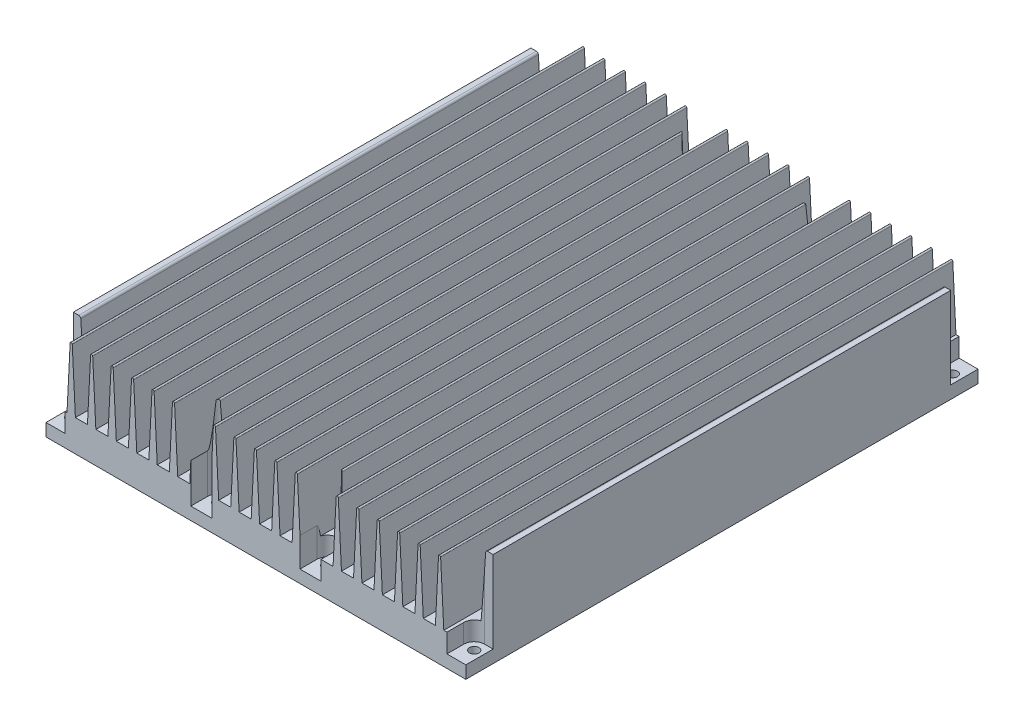
SolidWorks part; units mm, degrees
ref_plane "Спереди" through (0, 0, 0) normal (0, 0, 1) x (1, 0, 0)
ref_plane "Сверху" through (0, 0, 0) normal (0, 1, 0) x (1, 0, 0)
ref_plane "Справа" through (0, 0, 0) normal (1, 0, 0) x (0, 0, -1)
sketch "Эскиз1" plane through (0, 0, 0) normal (0, 0, 1) x (1, 0, 0)
  line L0 (0, 45) -> (2.5644, 45)
  line L1 (0, 0) -> (200, 0)
  line L2 (3.5622, 44.0665) -> (5.5, 15)
  line L3 (0, 45) -> (0, 0)
  line L4 (200, 45) -> (200, 0)
  line L5 (100, 63.7127) -> (100, -22.2582) construction
  line L8 (200, 45) -> (197.4356, 45)
  line L9 (196.4378, 44.0665) -> (194.5, 15)
  line L10 (5.5, 15) -> (194.5, 15)
  arc A0 (2.5644, 45) -> (3.5622, 44.0665) centre (2.5644, 44) cw
  arc A2 (197.4356, 45) -> (196.4378, 44.0665) centre (197.4356, 44) ccw
  point P18 (196.5, 45)
  dimension "D9" = 1
  dimension "D1" = 200
  dimension "D2" = 15
  dimension "D3" = 45
  dimension "D4" = 5.5
  dimension "D7" = 3.5
extrude "Вытянуть1" add sketch "Эскиз1" along normal blind 244
sketch "Эскиз2" plane through (0, 0, 244) normal (0, 0, 1) x (1, 0, 0)
  line L0 (194.5, 15) -> (5.5, 15) construction
  line L1 (11.5, 44.5) -> (10, 15)
  line L2 (12, 44.5) -> (12, 22.5548) construction
  line L3 (12.5, 44.5) -> (14, 15)
  line L4 (10, 15) -> (14, 15)
  line L6 (0, 45) -> (0, 0) construction
  arc A0 (11.5, 44.5) -> (12.5, 44.5) centre (12, 44.5) cw
  dimension "D1" = 30
  dimension "D3" = 0.5
  dimension "D2" = 4
  dimension "D4" = 12
  dimension "D5" = 1
extrude "Вытянуть3" add sketch "Эскиз2" against normal blind 244
pattern_curve "Кривая1" of "Вытянуть3" along edge at (100, 0, 0) parameters "D1"=19, "D3"=9.75, "D2"=1, "D4"=50
sketch "Эскиз3" plane through (0, 0, 0) normal (0, -1, 0) x (1, 0, 0)
  line L0 (11.9208, 236) -> (163.4793, 236) construction
  line L9 (4, 8) -> (74, 8) construction
  line L10 (-13.0453, 122) -> (213.0453, 122) construction
  line L11 (0, 244) -> (200, 244) construction
  line L12 (0, 0) -> (200, 0) construction
  line L13 (100, 122) -> (100, 199.2779) construction
  line L14 (0, 244) -> (0, 0) construction
  line L15 (200, 244) -> (200, 0) construction
  line L16 (4, 8) -> (4, 236) construction
  circle A0 centre (4, 236) radius 2.25
  circle A1 centre (74, 236) radius 2.25
  circle A2 centre (74, 8) radius 2.25
  circle A3 centre (4, 8) radius 2.25
  circle A4 centre (196, 8) radius 2.25
  circle A5 centre (126, 8) radius 2.25
  circle A6 centre (126, 236) radius 2.25
  circle A7 centre (196, 236) radius 2.25
  dimension "D2" = 70
  dimension "D4" = 4.5
  dimension "D1" = 228
  dimension "D3" = 70
  dimension "D5" = 4
extrude "Вырез-Вытянуть1" cut sketch "Эскиз3" against normal blind 50
ref_plane "Плоскость1" through (0, 6, 0) normal (0, -1, 0) x (1, 0, 0)
sketch "Эскиз6" plane through (0, 6, 0) normal (0, -1, 0) x (1, 0, 0)
  line L0 (-60.3162, 122) -> (260.3162, 122) construction
  line L1 (0, 244) -> (200, 244) construction
  line L2 (0, 0) -> (200, 0) construction
  line L3 (100, 122) -> (100, 228.6897) construction
  line L4 (0, 244) -> (0, 0) construction
  line L5 (200, 244) -> (200, 0) construction
  line L6 (9, 236) -> (9, 247.6253)
  line L7 (4, 231) -> (-6.1278, 231)
  line L8 (-6.1278, 231) -> (-6.1278, 247.6253)
  line L9 (-6.1278, 247.6253) -> (9, 247.6253)
  line L10 (69, 236) -> (69, 248.9831)
  line L11 (69, 248.9831) -> (79, 248.9831)
  line L12 (79, 248.9831) -> (79, 236)
  line L13 (121, 248.9831) -> (121, 236)
  line L14 (131, 248.9831) -> (121, 248.9831)
  line L15 (131, 236) -> (131, 248.9831)
  line L16 (206.1278, 247.6253) -> (191, 247.6253)
  line L17 (206.1278, 231) -> (206.1278, 247.6253)
  line L18 (196, 231) -> (206.1278, 231)
  line L19 (191, 236) -> (191, 247.6253)
  line L20 (191, 8) -> (191, -3.6253)
  line L21 (196, 13) -> (206.1278, 13)
  line L22 (206.1278, 13) -> (206.1278, -3.6253)
  line L23 (206.1278, -3.6253) -> (191, -3.6253)
  line L24 (131, 8) -> (131, -4.9831)
  line L25 (131, -4.9831) -> (121, -4.9831)
  line L26 (121, -4.9831) -> (121, 8)
  line L27 (79, -4.9831) -> (79, 8)
  line L28 (69, -4.9831) -> (79, -4.9831)
  line L29 (69, 8) -> (69, -4.9831)
  line L30 (-6.1278, -3.6253) -> (9, -3.6253)
  line L31 (-6.1278, 13) -> (-6.1278, -3.6253)
  line L32 (4, 13) -> (-6.1278, 13)
  line L33 (9, 8) -> (9, -3.6253)
  arc A0 (4, 231) -> (9, 236) centre (4, 236) ccw
  arc A1 (69, 236) -> (79, 236) centre (74, 236) ccw
  arc A2 (131, 236) -> (121, 236) centre (126, 236) cw
  arc A3 (196, 231) -> (191, 236) centre (196, 236) cw
  arc A4 (196, 13) -> (191, 8) centre (196, 8) ccw
  arc A5 (131, 8) -> (121, 8) centre (126, 8) ccw
  arc A6 (69, 8) -> (79, 8) centre (74, 8) cw
  arc A7 (4, 13) -> (9, 8) centre (4, 8) cw
  dimension "D1" = 10
  dimension "D2" = 10
extrude "Вырез-Вытянуть3" cut sketch "Эскиз6" against normal blind 80
sketch "Эскиз8" plane through (133.2401, 0, 310.1491) normal (0, -1, 0) x (-1, 0, 0)
  line L0 (93.2401, 227.1491) -> (93.2401, 83.3966) construction
  line L2 (133.2401, 310.1491) -> (-66.7599, 310.1491) construction
  line L3 (47.2401, 237.1491) -> (113.2401, 237.1491) construction
  line L4 (47.2401, 237.1491) -> (47.2401, 285.1491) construction
  line L5 (47.2401, 285.1491) -> (113.2401, 285.1491) construction
  line L6 (113.2401, 237.1491) -> (113.2401, 285.1491) construction
  line L9 (33.2401, 159.5534) -> (33.2401, 43.0769) construction
  circle A0 centre (93.2401, 92.1491) radius 1.6
  circle A1 centre (93.2401, 227.1491) radius 1.6
  circle A2 centre (53.4901, 223.5491) radius 1.6
  circle A3 centre (53.4901, 139.7491) radius 1.6
  circle A4 centre (56.2401, 100.6491) radius 1.3
  circle A5 centre (113.2401, 285.1491) radius 1.6
  circle A6 centre (113.2401, 237.1491) radius 1.6
  circle A7 centre (47.2401, 237.1491) radius 1.6
  circle A8 centre (47.2401, 285.1491) radius 1.6
  circle A9 centre (59.2401, 74.1491) radius 2.25 construction
  circle A10 centre (7.2401, 74.1491) radius 2.25 construction
  dimension "D1" = 3.2
  dimension "D3" = 3.2
  dimension "D4" = 39.75
  dimension "D5" = 39.75
  dimension "D6" = 8.5
  dimension "D7" = 47.6
  dimension "D8" = 3.6
  dimension "D9" = 135
  dimension "D10" = 60
  dimension "D11" = 83
  dimension "D16" = 2.6
  dimension "D17" = 3.2
  dimension "D15" = 20
  dimension "D2" = 37
  dimension "D12" = 66
  dimension "D13" = 48
  dimension "D14" = 25
extrude "Вырез-Вытянуть4" cut sketch "Эскиз8" against normal blind 10
cosmetic thread "Условное изображение резьбы11" parameters "D2"=4
cosmetic thread "Условное изображение резьбы12" parameters "D2"=4
cosmetic thread "Условное изображение резьбы13" parameters "D2"=4
cosmetic thread "Условное изображение резьбы14" parameters "D2"=4
cosmetic thread "Условное изображение резьбы15" parameters "D2"=3
cosmetic thread "Условное изображение резьбы16" parameters "D2"=4
cosmetic thread "Условное изображение резьбы17" parameters "D2"=4
cosmetic thread "Условное изображение резьбы18" parameters "D2"=4
cosmetic thread "Условное изображение резьбы19" parameters "D2"=4
sketch "Эскиз10" plane through (-5.7236, 0, -26.359) normal (0, -1, 0) x (1, 0, 0)
  line L0 (165.7236, 244.359) -> (165.7236, 165.0862) construction
  line L1 (125.4736, 196.759) -> (125.4736, 206.4606) construction
  line L2 (105.7236, 289.9001) -> (105.7236, 174.1685) construction
  line L3 (29.3326, 176.859) -> (120.0513, 176.859) construction
  line L4 (85.4736, 112.959) -> (140.2236, 112.959) construction
  line L5 (5.7236, 26.359) -> (205.7236, 26.359) construction
  circle A0 centre (139.2236, 207.359) radius 2.6
  circle A1 centre (165.7236, 244.359) radius 1.6
  circle A2 centre (165.7236, 109.359) radius 1.6
  circle A3 centre (125.4736, 196.759) radius 1.6
  circle A4 centre (125.4736, 112.959) radius 1.6
  circle A5 centre (45.7236, 244.359) radius 1.6 construction
  circle A6 centre (45.7236, 109.359) radius 1.6 construction
  circle A7 centre (79.7236, 262.359) radius 2.25 construction
  circle A8 centre (131.7236, 262.359) radius 2.25 construction
  circle A11 centre (45.7236, 244.359) radius 1.6 construction
  circle A12 centre (45.7236, 109.359) radius 1.6 construction
  dimension "D2" = 5.2
  dimension "D4" = 181
  dimension "D3" = 19.75
  dimension "D1" = 33.5
extrude "Вырез-Вытянуть5" cut sketch "Эскиз10" against normal blind 6
cosmetic thread "Условное изображение резьбы20" parameters "D2"=4
cosmetic thread "Условное изображение резьбы21" parameters "D2"=4
cosmetic thread "Условное изображение резьбы22" parameters "D2"=4
cosmetic thread "Условное изображение резьбы23" parameters "D2"=4
sketch "Эскиз12" plane through (193.6475, 0, 525.6721) normal (0, -1, 0) x (-1, 0, 0)
  line L0 (55.8166, 483.1721) -> (23.712, 483.1721) construction
  line L1 (48.6475, 490.8953) -> (48.6475, 529.7425) construction
  line L4 (193.6475, 525.6721) -> (-6.3525, 525.6721) construction
  line L5 (93.6475, 437.7034) -> (93.6475, 540.3004) construction
  line L7 (107.6475, 500.6721) -> (37.9581, 500.6721) construction
  circle A0 centre (10.6475, 425.6721) radius 2.1
  circle A1 centre (18.6475, 500.6721) radius 1.6
  circle A2 centre (78.6475, 500.6721) radius 1.6
  circle A3 centre (119.6475, 517.6721) radius 2.25 construction
  circle A4 centre (78.6475, 465.6721) radius 1.6
  circle A5 centre (18.6475, 465.6721) radius 1.6
  circle A6 centre (67.6475, 517.6721) radius 2.25 construction
  dimension "D1" = 4.2
  dimension "D3" = 15
  dimension "D5" = 100
  dimension "D6" = 83
  dimension "D8" = 60
  dimension "D2" = 3.2
  dimension "D9" = 17.5
extrude "Вырез-Вытянуть6" cut sketch "Эскиз12" against normal blind 10
cosmetic thread "Условное изображение резьбы24" parameters "D2"=5
cosmetic thread "Условное изображение резьбы25" parameters "D2"=5
cosmetic thread "Условное изображение резьбы26" parameters "D2"=4
cosmetic thread "Условное изображение резьбы27" parameters "D2"=4
cosmetic thread "Условное изображение резьбы28" parameters "D2"=4
cosmetic thread "Условное изображение резьбы29" parameters "D2"=4
